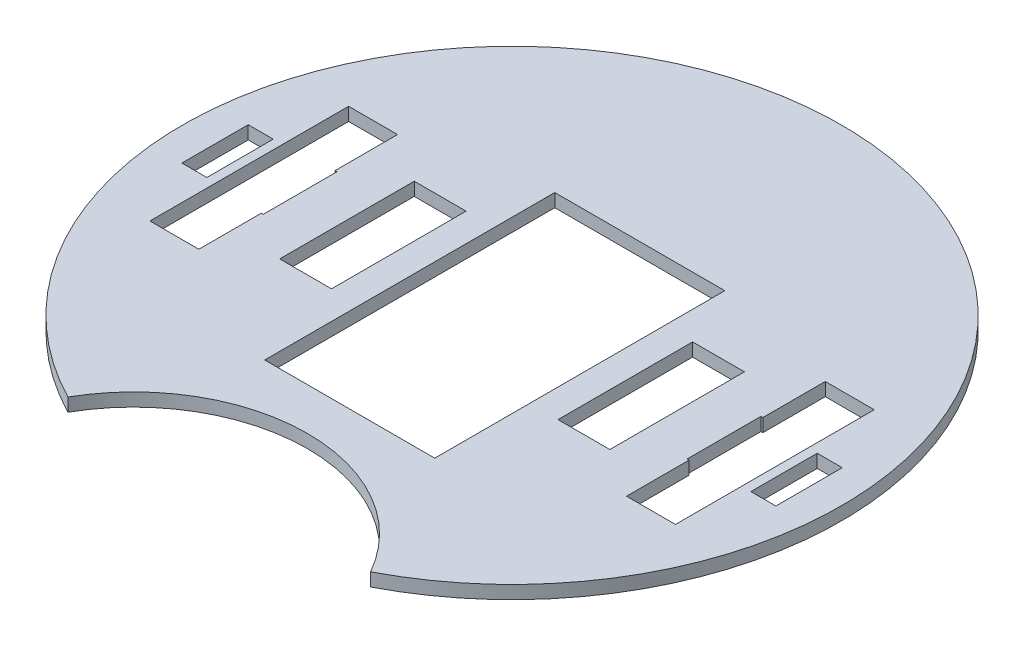
SolidWorks part; units mm, degrees
ref_plane "Front Plane" through (0, 0, 0) normal (0, 0, 1) x (1, 0, 0)
ref_plane "Top Plane" through (0, 0, 0) normal (0, 1, 0) x (1, 0, 0)
ref_plane "Right Plane" through (0, 0, 0) normal (1, 0, 0) x (0, 0, -1)
sketch "Sketch1" plane through (0, 0, 0) normal (0, 1, 0) x (1, 0, 0)
  line L0 (0, -83.2398) -> (-33.2911, -64.4046) construction
  line L1 (0, -83.2398) -> (0, 0) construction
  arc A0 (33.2911, -64.4046) -> (-33.2911, -64.4046) centre (0, 0) ccw
  arc A1 (33.2911, -64.4046) -> (-33.2911, -64.4046) centre (0, -83.2398) ccw
  dimension "D1" = 145
  dimension "D2" = 76.5
  dimension "D3" = 60.5
extrude "Boss-Extrude1" add sketch "Sketch1" along normal blind 2.9
sketch "solenoid placement" plane through (0, 2.9, 0) normal (0, 1, 0) x (1, 0, 0)
  line L0 (0, 0) -> (0, -36) construction
  line L1 (0, -36) -> (0, -44.9898) construction
  line L2 (-19, -36) -> (19, -36) construction
  line L3 (-19, -36) -> (-19, 28.4) construction
  line L4 (-19, 28.4) -> (19, 28.4) construction
  line L5 (19, -36) -> (19, 28.4) construction
  line L6 (-18.7, 28.1) -> (18.7, 28.1)
  line L7 (18.7, -35.7) -> (18.7, 28.1)
  line L8 (-18.7, -35.7) -> (18.7, -35.7)
  line L9 (-18.7, -35.7) -> (-18.7, 28.1)
  circle A1 centre (0, 0) radius 72.5 construction
  arc A2 (33.2911, -64.4046) -> (-33.2911, -64.4046) centre (0, 0) ccw construction
  arc A3 (33.2911, -64.4046) -> (-33.2911, -64.4046) centre (0, -83.2398) ccw construction
  dimension "D1" = 64.4
  dimension "D2" = 36
  dimension "D3" = 0.3
  dimension "D4" = 38
extrude "Cut-Extrude1" cut sketch "solenoid placement" against normal through all
sketch "Sketch2" plane through (0, 2.9, 0) normal (0, 1, 0) x (1, 0, 0)
  line L0 (47.34, -21.5538) -> (47.34, 21.5538) construction
  line L1 (-57.5, -21.5538) -> (-47.34, -21.5538) construction
  line L2 (-57.5, -21.5538) -> (-57.5, 21.5538) construction
  line L3 (-57.5, 21.5538) -> (-47.34, 21.5538) construction
  line L4 (-47.34, -21.5538) -> (-47.34, 21.5538) construction
  line L5 (57.5, 21.5538) -> (47.34, 21.5538) construction
  line L6 (57.5, -21.5538) -> (57.5, 21.5538) construction
  line L7 (57.5, -21.5538) -> (47.34, -21.5538) construction
  line L8 (57.8, -21.8538) -> (57.8, 21.8538)
  line L9 (57.8, -21.8538) -> (47.04, -21.8538)
  line L10 (47.04, -21.8538) -> (47.04, 21.8538)
  line L11 (57.8, 21.8538) -> (47.04, 21.8538)
  line L12 (0, 0) -> (0, 72.5) construction
  line L13 (-57.8, 21.8538) -> (-47.04, 21.8538)
  line L14 (-47.04, -21.8538) -> (-47.04, 21.8538)
  line L15 (-57.8, -21.8538) -> (-47.04, -21.8538)
  line L16 (-57.8, -21.8538) -> (-57.8, 21.8538)
  arc A0 (33.2911, -64.4046) -> (-33.2911, -64.4046) centre (0, 0) ccw construction
  dimension "D1" = 0.3
extrude "Cut-Extrude2" cut sketch "Sketch2" against normal through all
sketch "Sketch3" plane through (0, 2.9, 0) normal (0, 1, 0) x (1, 0, 0)
  line L0 (-36.31, -14.8) -> (-24.91, -14.8)
  line L1 (-36.51, -15) -> (-24.71, -15) construction
  line L2 (-36.51, -15) -> (-36.51, 15) construction
  line L3 (-36.51, 15) -> (-24.71, 15) construction
  line L4 (-24.71, -15) -> (-24.71, 15) construction
  line L5 (-24.91, -14.8) -> (-24.91, 14.8)
  line L6 (-36.31, 14.8) -> (-24.91, 14.8)
  line L7 (-36.31, -14.8) -> (-36.31, 14.8)
  line L8 (0, 0) -> (0, 72.5) construction
  line L9 (24.71, -15) -> (24.71, 15) construction
  line L10 (36.51, 15) -> (24.71, 15) construction
  line L11 (36.51, -15) -> (36.51, 15) construction
  line L12 (36.51, -15) -> (24.71, -15) construction
  line L13 (36.31, -14.8) -> (36.31, 14.8)
  line L14 (36.31, 14.8) -> (24.91, 14.8)
  line L15 (24.91, -14.8) -> (24.91, 14.8)
  line L16 (36.31, -14.8) -> (24.91, -14.8)
  arc A0 (33.2911, -64.4046) -> (-33.2911, -64.4046) centre (0, 0) ccw construction
  dimension "D1" = 0.2
extrude "Cut-Extrude3" cut sketch "Sketch3" against normal through all
sketch "Sketch5" plane through (0, 2.9, 0) normal (0, 1, 0) x (1, 0, 0)
  line L1 (-65.33, 7.3) -> (-59.83, 7.3)
  line L2 (-65.53, 7.5) -> (-59.63, 7.5) construction
  line L3 (-65.53, 7.5) -> (-65.53, -7.5) construction
  line L4 (-65.53, -7.5) -> (-59.63, -7.5) construction
  line L6 (-59.63, 7.5) -> (-59.63, -7.5) construction
  line L7 (-59.83, 7.3) -> (-59.83, -7.3)
  line L8 (-65.33, -7.3) -> (-59.83, -7.3)
  line L9 (-65.33, 7.3) -> (-65.33, -7.3)
  line L10 (59.63, 7.5) -> (59.63, -7.5) construction
  line L11 (65.53, -7.5) -> (59.63, -7.5) construction
  line L12 (65.53, 7.5) -> (65.53, -7.5) construction
  line L13 (65.53, 7.5) -> (59.63, 7.5) construction
  line L14 (65.33, 7.3) -> (65.33, -7.3)
  line L15 (65.33, -7.3) -> (59.83, -7.3)
  line L28 (0, 0) -> (0, 72.5) construction
  line L29 (59.83, 7.3) -> (59.83, -7.3)
  line L30 (65.33, 7.3) -> (59.83, 7.3)
  arc A0 (33.2911, -64.4046) -> (-33.2911, -64.4046) centre (0, 0) ccw construction
  dimension "D1" = 0.2
extrude "Cut-Extrude4" cut sketch "Sketch5" against normal through all
sketch "Sketch6" plane through (0, 2.9, 0) normal (0, 1, 0) x (1, 0, 0)
  line L0 (-47.04, -21.8538) -> (-47.04, 21.8538) construction
  line L1 (-47.04, 7.8128) -> (-46.91, 7.8128) construction
  line L2 (-47.04, 7.8128) -> (-47.04, -7.8128) construction
  line L3 (-47.04, -7.8128) -> (-46.91, -7.8128) construction
  line L4 (-46.91, 7.8128) -> (-46.91, -7.8128) construction
  line L9 (-47.34, 8.1128) -> (-46.61, 8.1128)
  line L10 (-46.61, 8.1128) -> (-46.61, -8.1128)
  line L11 (-47.34, -8.1128) -> (-46.61, -8.1128)
  line L12 (-47.34, 8.1128) -> (-47.34, -8.1128)
  line L13 (0, 0) -> (0, 72.5) construction
  line L14 (46.91, 7.8128) -> (46.91, -7.8128) construction
  line L15 (47.04, -7.8128) -> (46.91, -7.8128) construction
  line L16 (47.04, 7.8128) -> (47.04, -7.8128) construction
  line L17 (47.04, 7.8128) -> (46.91, 7.8128) construction
  line L18 (47.34, 8.1128) -> (47.34, -8.1128)
  line L19 (47.34, -8.1128) -> (46.61, -8.1128)
  line L20 (46.61, 8.1128) -> (46.61, -8.1128)
  line L21 (47.34, 8.1128) -> (46.61, 8.1128)
  arc A0 (33.2911, -64.4046) -> (-33.2911, -64.4046) centre (0, 0) ccw construction
  dimension "D1" = 0.3
extrude "Cut-Extrude5" cut sketch "Sketch6" against normal through all
equation "\"smallPulleyTeeth\"= 15"
equation "\"largePulleyTeeth\"= 40"
equation "\"eighthThick\"= 2.9mm"
equation "\"sixteenthThick\"= 1.7mm"
equation "\"quarterThick\"=5.9mm"
equation "\"OD\"= 145mm"
equation "\"puckAngle\"= 60.5deg"
equation "\"D1@Sketch1\"=\"OD\""
equation "\"puckDiam\"= 76.5mm"
equation "\"D2@Sketch1\"=\"puckDiam\""
equation "\"D3@Sketch1\"=\"puckAngle\""
equation "\"D1@Boss-Extrude1\"=\"eighthThick\""
equation "\"axlePress\"= 5.9mm"
equation "\"press\"= 0.2mm"
equation "\"D1@Sketch3\"=\"press\""
equation "\"wheelClear\"= 0.3mm"
equation "\"D1@Sketch2\"=\"wheelClear\""
equation "\"D1@Sketch6\"=\"wheelClear\""
equation "\"D1@Sketch5\"=\"press\""
